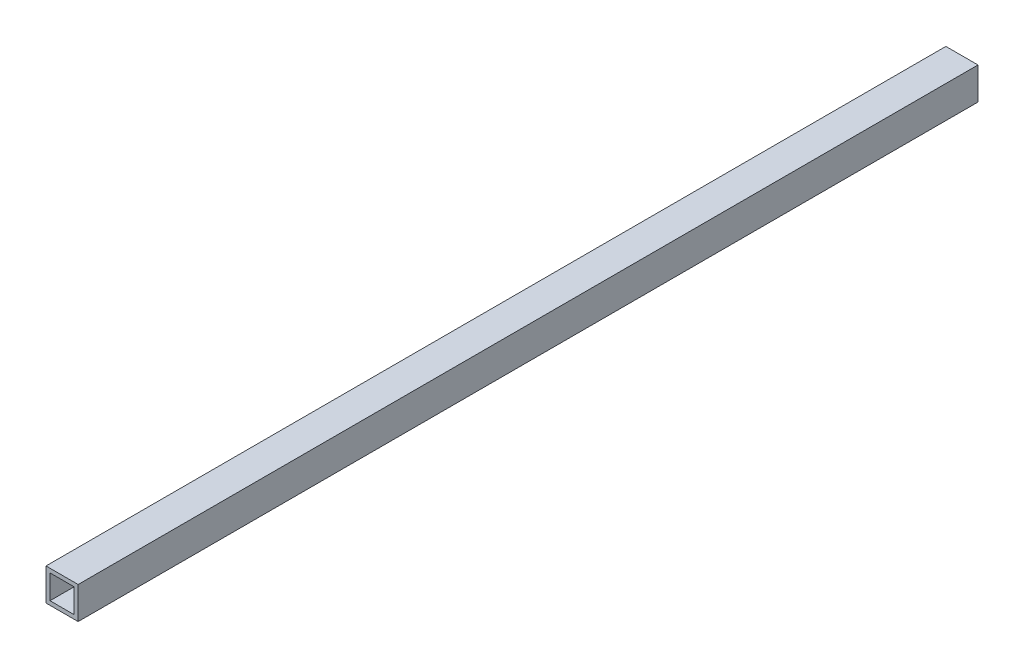
SolidWorks part; units mm, degrees
material "6061-T6 (SS)"
ref_plane "Front Plane" through (0, 0, 0) normal (0, 0, 1) x (1, 0, 0)
ref_plane "Top Plane" through (0, 0, 0) normal (0, 1, 0) x (1, 0, 0)
ref_plane "Right Plane" through (0, 0, 0) normal (1, 0, 0) x (0, 0, -1)
sketch "Sketch1" plane through (0, 0, 0) normal (0, 0, 1) x (1, 0, 0)
  line L0 (342.9, 66.675) -> (317.5, 66.675) construction
  line L1 (317.5, 92.075) -> (317.5, 66.675) construction
  line L2 (342.9, 92.075) -> (317.5, 92.075) construction
  line L3 (342.9, 92.075) -> (342.9, 66.675) construction
  line L4 (342.9, 66.675) -> (317.5, 66.675)
  line L5 (317.5, 92.075) -> (317.5, 66.675)
  line L6 (342.9, 92.075) -> (317.5, 92.075)
  line L7 (342.9, 92.075) -> (342.9, 66.675)
  line L8 (339.725, 88.9) -> (320.675, 88.9)
  line L9 (320.675, 88.9) -> (320.675, 69.85)
  line L10 (339.725, 69.85) -> (320.675, 69.85)
  line L11 (339.725, 88.9) -> (339.725, 69.85)
  dimension "D1" = 3.175
extrude "Boss-Extrude1" add sketch "Sketch1" along normal up to vertex (355.6 mm away) and the other way up to vertex (355.6 mm away)
